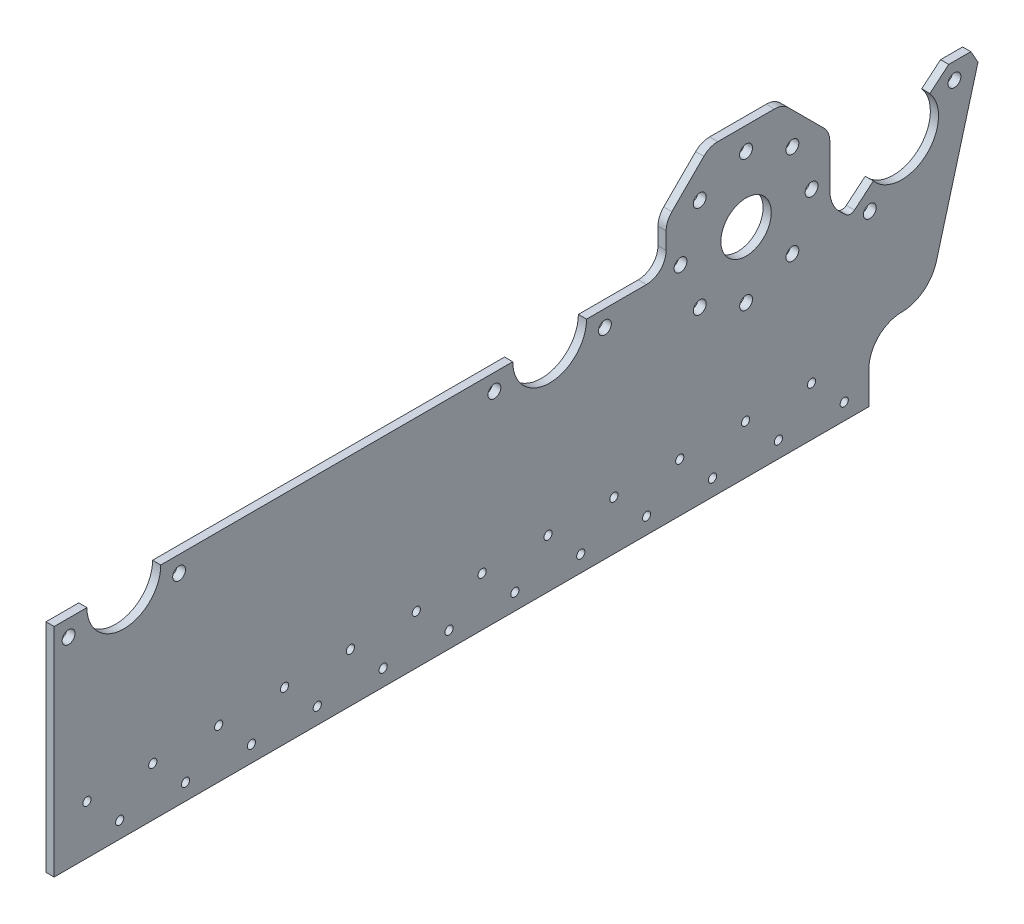
SolidWorks part; units mm, degrees
material "6061 Alloy"
ref_plane "Front Plane" through (0, 0, 0) normal (0, 0, 1) x (1, 0, 0)
ref_plane "Top Plane" through (0, 0, 0) normal (0, 1, 0) x (1, 0, 0)
ref_plane "Right Plane" through (0, 0, 0) normal (1, 0, 0) x (0, 0, -1)
sketch "Sketch1" plane through (0, 0, 0) normal (1, 0, 0) x (0, 0, -1)
  line L0 (-12.7, -12.7) -> (-328.6379, -12.7)
  line L1 (-328.6379, -12.7) -> (-328.6379, 71.4629)
  line L2 (-328.6379, 71.4629) -> (-315.9379, 71.4629)
  line L3 (-287.3121, 71.4629) -> (-150.8125, 71.4629)
  line L5 (10.9643, 80.6631) -> (18.2626, 86.7871)
  line L7 (-328.6379, 12.7) -> (13.4731, 12.7) construction
  line L8 (-12.7, -12.7) -> (-12.7, 0)
  line L9 (0, 12.4079) -> (0, 12.7) construction
  line L10 (13.4731, 22.9772) -> (30.9626, 86.7871)
  line L12 (-10.9643, 62.2627) -> (10.9643, 80.6631) construction
  line L13 (18.2626, 86.7871) -> (30.9626, 86.7871)
  line L14 (-122.1867, 71.4629) -> (-91.313, 71.4629)
  line L15 (-10.9643, 62.2627) -> (-18.2626, 56.1387)
  line L16 (-21.6532, 56.2511) -> (-23.945, 58.4485)
  line L18 (0, 71.4629) -> (-136.4996, 71.4629) construction
  line L19 (-328.6379, 15.875) -> (13.4731, 15.875) construction
  line L20 (-27.8553, 67.6154) -> (-27.8553, 87.307)
  line L21 (-27.8553, 87.307) -> (-46.1742, 105.6259)
  line L22 (-46.1742, 105.6259) -> (-74.4758, 105.6259)
  line L23 (-91.313, 88.7887) -> (-91.313, 71.4629)
  line L25 (-74.4758, 105.6259) -> (-91.313, 88.7887)
  arc A3 (0, 12.7) -> (13.4731, 22.9772) centre (0, 26.67) ccw
  arc A4 (0, 12.7) -> (-12.7, 0) centre (0, 0) ccw
  circle A5 centre (0, 0) radius 12.4079 construction
  arc A6 (-315.9379, 71.4629) -> (-287.3121, 71.4629) centre (-301.625, 71.4629) ccw
  arc A7 (-150.8125, 71.4629) -> (-122.1867, 71.4629) centre (-136.4996, 71.4629) ccw
  arc A8 (-10.9643, 62.2627) -> (10.9643, 80.6631) centre (0, 71.4629) ccw
  arc A9 (-18.2626, 56.1387) -> (-21.6532, 56.2511) centre (-19.8953, 58.0845) cw
  circle A11 centre (-60.325, 71.4629) radius 9.779
  arc A14 (-27.8553, 67.6154) -> (-23.945, 58.4485) centre (-15.1553, 67.6154) ccw
  circle A15 centre (-60.325, 71.4629) radius 25.4 construction
  circle A16 centre (-60.325, 96.8629) radius 2.413
  circle A17 centre (-42.3645, 89.4234) radius 2.413
  circle A18 centre (-34.925, 71.4629) radius 2.413
  circle A19 centre (-42.3645, 53.5024) radius 2.413
  circle A20 centre (-60.325, 46.0629) radius 2.413
  circle A21 centre (-78.2855, 53.5024) radius 2.413
  circle A22 centre (-85.725, 71.4629) radius 2.413
  circle A23 centre (-78.2855, 89.4234) radius 2.413
  point P4 (-170.669, -12.7)
  point P44 (-82.018, 71.4629)
  point P51 (-27.8553, 62.1979)
  point P60 (-60.325, 71.4629)
  dimension "D1" = 25.4
  dimension "D3" = 12.7
  dimension "D5" = 28.6258
  dimension "D6" = 3.175
  dimension "D7" = 13.97
  dimension "D8" = 12.7
  dimension "D10" = 24.8158
  dimension "D13" = 9.5273
  dimension "D14" = 140
  dimension "D15" = 2.54
  dimension "D16" = 50.8
  dimension "D17" = 60.325
  dimension "D18" = 41.275
  dimension "D24" = 3.175
  dimension "D26" = 12.7
  dimension "D19" = 4.826
  dimension "D25" = 6.35
  dimension "D29" = 6.35
  dimension "D20" = 4.6567
  dimension "D30" = 9.779
  dimension "D2" = 0
  dimension "D4" = 12.7
  dimension "D9" = 12.7
  dimension "D11" = 301.625
  dimension "D12" = 301.625
  dimension "D21" = 8
  dimension "D22" = 45
  dimension "D23" = 45
  dimension "D27" = 6.35
  dimension "D28" = 3.175
extrude "Boss-Extrude1" add sketch "Sketch1" along normal blind 3.175
hole_wizard "#10 Clearance Hole1" positions "Sketch2" profile "Sketch3" hole size "#10" standard "ANSI Inch" end condition through all
sketch "Sketch2" plane through (3.175, 0, 0) normal (1, 0, 0) x (0, 0, -1)
  line L0 (-323.0562, 65.1129) -> (-280.1937, 65.1129) construction
  line L2 (-157.9309, 65.1129) -> (-115.0683, 65.1129) construction
  line L4 (-12.3356, 52.8228) -> (20.499, 80.3743) construction
  line L6 (-315.9379, 71.4629) -> (-328.6379, 71.4629) construction
  line L7 (-301.625, 65.1129) -> (-301.625, 71.4629) construction
  line L9 (-136.4996, 71.4629) -> (-136.4996, 65.1129) construction
  line L11 (0, 71.4629) -> (4.0817, 66.5985) construction
  line L14 (18.2626, 86.7871) -> (10.9643, 80.6631) construction
  line L15 (18.2626, 86.7871) -> (10.9643, 80.6631) construction
  point P0 (-323.0562, 65.1129)
  point P2 (-280.1938, 65.1129)
  point P4 (-157.9309, 65.1129)
  point P6 (-115.0683, 65.1129)
  point P8 (-12.3356, 52.8228)
  point P10 (20.499, 80.3743)
  dimension "D1" = 42.8625
  dimension "D2" = 6.35
  dimension "D3" = 6.35
sketch "Sketch3" plane through (3.175, 65.1129, 323.0562) normal (0, 1, 0) x (0, 0, -1)
  line L0 (0, 0) -> (0, 3.175)
  line L1 (0, 3.175) -> (2.4892, 3.175)
  line L2 (2.4892, 3.175) -> (2.4892, 0)
  line L5 (2.4892, 0) -> (0, 0)
  line L11 (0, -6.35) -> (0, 107.95) construction
  dimension "Thru Hole Dia." = 4.9784
  dimension "Thru Hole Depth" = 3.175
hole_wizard "#10 Clearance Hole2" positions "Sketch5" profile "Sketch6" hole size "#10" standard "ANSI Inch"
sketch "Sketch5" plane through (3.175, 0, 0) normal (1, 0, 0) x (0, 0, -1)
  point P0 (-60.325, 96.8629)
  point P3 (-42.3645, 89.4234)
  point P6 (-34.925, 71.4629)
  point P9 (-42.3645, 53.5024)
  point P12 (-60.325, 46.0629)
  point P15 (-78.2855, 53.5024)
  point P18 (-85.725, 71.4629)
  point P21 (-78.2855, 89.4234)
sketch "Sketch6" plane through (3.175, 96.8629, 60.325) normal (0, 1, 0) x (0, 0, -1)
  line L0 (0, 0) -> (0, 4.6707)
  line L1 (0, 4.6707) -> (2.4892, 3.175)
  line L2 (2.4892, 3.175) -> (2.4892, 0)
  line L5 (2.4892, 0) -> (0, 0)
  line L10 (0, 4.6707) -> (-2.4892, 3.175) construction
  line L11 (0, -6.35) -> (0, 107.95) construction
  dimension "Hole Dia." = 4.9784
  dimension "Hole Depth" = 3.175
  dimension "Drill Angle" = 118
chamfer "Chamfer1" distance 5.08 angle 45 1 edges at (1.5875, 86.7871, -30.9626)
fillet "Fillet1" radius 7.62 5 edges at (1.5875, 87.307, 27.8553) (1.5875, 105.6259, 46.1742) (1.5875, 105.6259, 74.4758) (1.5875, 88.7887, 91.313) (1.5875, 71.4629, 91.313)
sketch "Sketch7" plane through (0, 0, 0) normal (-1, 0, 0) x (0, 0, 1)
  circle A0 centre (315.9379, 6.35) radius 1.5875 construction
  circle A1 centre (303.2379, -6.35) radius 1.5875 construction
  circle A2 centre (290.3936, 6.35) radius 1.5875 construction
  circle A3 centre (277.6936, -6.35) radius 1.5875 construction
  circle A4 centre (264.8493, 6.35) radius 1.5875 construction
  circle A5 centre (252.1493, -6.35) radius 1.5875 construction
  circle A6 centre (239.3049, 6.35) radius 1.5875 construction
  circle A7 centre (226.6049, -6.35) radius 1.5875 construction
  circle A8 centre (213.7606, 6.35) radius 1.5875 construction
  circle A9 centre (201.0606, -6.35) radius 1.5875 construction
  circle A10 centre (188.2163, 6.35) radius 1.5875 construction
  circle A11 centre (175.5163, -6.35) radius 1.5875 construction
  circle A12 centre (162.672, 6.35) radius 1.5875 construction
  circle A13 centre (149.972, -6.35) radius 1.5875 construction
  circle A14 centre (137.1277, 6.35) radius 1.5875 construction
  circle A15 centre (124.4277, -6.35) radius 1.5875 construction
  circle A16 centre (111.5834, 6.35) radius 1.5875 construction
  circle A17 centre (98.8834, -6.35) radius 1.5875 construction
  circle A18 centre (86.039, 6.35) radius 1.5875 construction
  circle A19 centre (73.339, -6.35) radius 1.5875 construction
  circle A20 centre (60.4947, 6.35) radius 1.5875 construction
  circle A21 centre (47.7947, -6.35) radius 1.5875 construction
  circle A22 centre (34.9504, 6.35) radius 1.5875 construction
  circle A23 centre (22.2504, -6.35) radius 1.5875 construction
  circle A24 centre (315.9379, 6.35) radius 1.5875
  circle A25 centre (303.2379, -6.35) radius 1.5875
  circle A26 centre (290.3936, 6.35) radius 1.5875
  circle A27 centre (277.6936, -6.35) radius 1.5875
  circle A28 centre (264.8493, 6.35) radius 1.5875
  circle A29 centre (252.1493, -6.35) radius 1.5875
  circle A30 centre (239.3049, 6.35) radius 1.5875
  circle A31 centre (226.6049, -6.35) radius 1.5875
  circle A32 centre (213.7606, 6.35) radius 1.5875
  circle A33 centre (201.0606, -6.35) radius 1.5875
  circle A34 centre (188.2163, 6.35) radius 1.5875
  circle A35 centre (175.5163, -6.35) radius 1.5875
  circle A36 centre (162.672, 6.35) radius 1.5875
  circle A37 centre (149.972, -6.35) radius 1.5875
  circle A38 centre (137.1277, 6.35) radius 1.5875
  circle A39 centre (124.4277, -6.35) radius 1.5875
  circle A40 centre (111.5834, 6.35) radius 1.5875
  circle A41 centre (98.8834, -6.35) radius 1.5875
  circle A42 centre (86.039, 6.35) radius 1.5875
  circle A43 centre (73.339, -6.35) radius 1.5875
  circle A44 centre (60.4947, 6.35) radius 1.5875
  circle A45 centre (47.7947, -6.35) radius 1.5875
  circle A46 centre (34.9504, 6.35) radius 1.5875
  circle A47 centre (22.2504, -6.35) radius 1.5875
extrude "Cut-Extrude1" cut sketch "Sketch7" against normal through all
